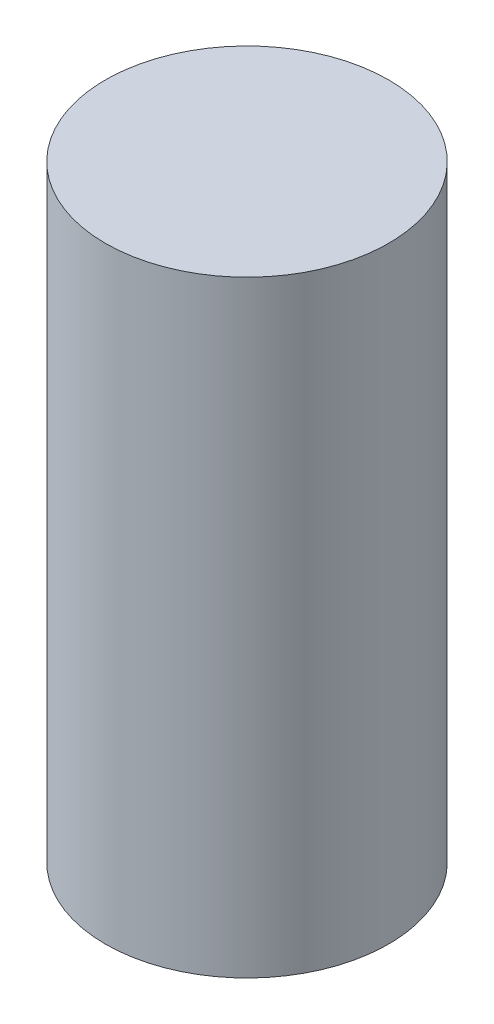
SolidWorks part; units mm, degrees
ref_plane "정면" through (0, 0, 0) normal (0, 0, 1) x (1, 0, 0)
ref_plane "윗면" through (0, 0, 0) normal (0, 1, 0) x (1, 0, 0)
ref_plane "우측면" through (0, 0, 0) normal (1, 0, 0) x (0, 0, -1)
sketch "Sketch1" plane through (0, 0, 0) normal (0, 1, 0) x (1, 0, 0)
  circle A0 centre (0, 0) radius 3.5
  dimension "D1" = 7
extrude "Boss-Extrude1" add sketch "Sketch1" along normal blind 15
